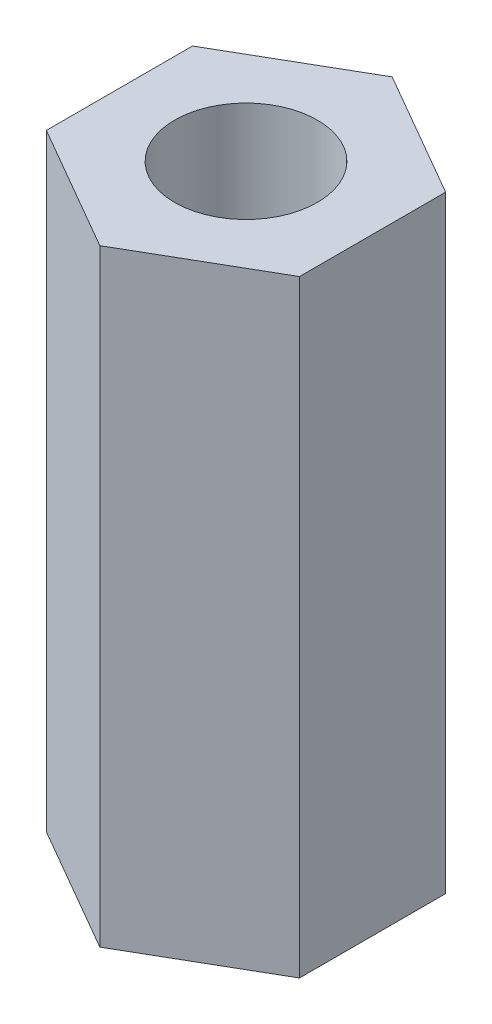
SolidWorks part; units mm, degrees
ref_plane "Front Plane" through (0, 0, 0) normal (0, 0, 1) x (1, 0, 0)
ref_plane "Top Plane" through (0, 0, 0) normal (0, 1, 0) x (1, 0, 0)
ref_plane "Right Plane" through (0, 0, 0) normal (1, 0, 0) x (0, 0, -1)
sketch "Sketch1" plane through (0, 0, 0) normal (0, 1, 0) x (1, 0, 0)
  line L0 (0, 2.887) -> (2.5002, 1.4435)
  line L1 (2.5002, 1.4435) -> (2.5002, -1.4435)
  line L2 (2.5002, -1.4435) -> (0, -2.887)
  line L3 (0, -2.887) -> (-2.5002, -1.4435)
  line L4 (-2.5002, -1.4435) -> (-2.5002, 1.4435)
  line L5 (-2.5002, 1.4435) -> (0, 2.887)
  circle A0 centre (0, 0) radius 1.41
  dimension "D2" = 2.82
  dimension "D3" = 2.887
extrude "Boss-Extrude1" add sketch "Sketch1" along normal blind 12
